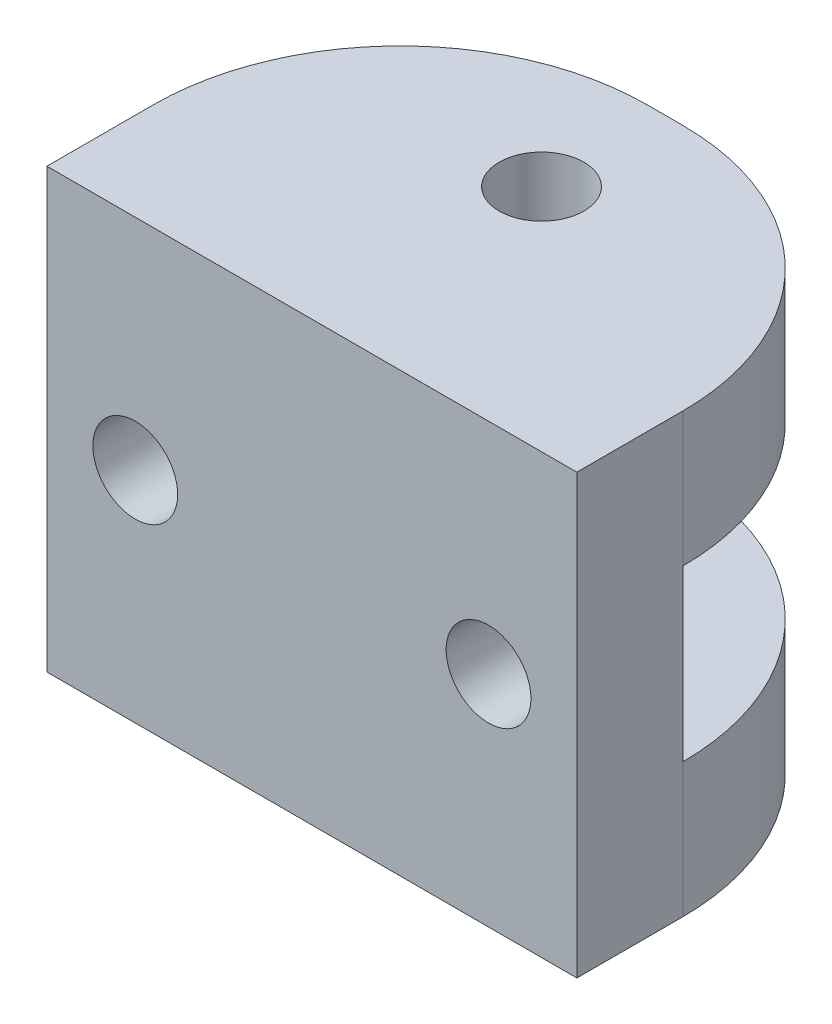
SolidWorks part; units mm, degrees
ref_plane "Front Plane" through (0, 0, 0) normal (0, 0, 1) x (1, 0, 0)
ref_plane "Top Plane" through (0, 0, 0) normal (0, 1, 0) x (1, 0, 0)
ref_plane "Right Plane" through (0, 0, 0) normal (1, 0, 0) x (0, 0, -1)
sketch "Sketch1" plane through (0, 0, 0) normal (1, 0, 0) x (0, 0, -1)
  line L0 (50, 62) -> (50, 43)
  line L1 (0, 0) -> (50, 0)
  line L2 (0, 0) -> (0, 62)
  line L3 (0, 62) -> (50, 62)
  line L5 (50, 43) -> (15, 43)
  line L6 (15, 43) -> (15, 19)
  line L7 (15, 19) -> (50, 19)
  line L8 (50, 19) -> (50, 0)
  dimension "D1" = 24
  dimension "D2" = 62
  dimension "D3" = 35
  dimension "D4" = 50
extrude "Boss-Extrude1" add sketch "Sketch1" along normal blind 75
sketch "Sketch2" plane through (0, 0, 0) normal (0, 0, 1) x (1, 0, 0)
  line L0 (0, 31) -> (75, 31) construction
  line L1 (0, 62) -> (0, 0) construction
  line L2 (75, 62) -> (75, 0) construction
  circle A0 centre (62.5, 31) radius 6
  circle A1 centre (12.5, 31) radius 6
  point P10 (37.5, 31)
  dimension "D3" = 12
  dimension "D1" = 50
  dimension "D2" = 25
extrude "Cut-Extrude1" cut sketch "Sketch2" against normal through all
sketch "Sketch3" plane through (0, 62, 0) normal (0, 1, 0) x (1, 0, 0)
  line L0 (0, 32.5) -> (75, 32.5) construction
  line L1 (0, 50) -> (0, 0) construction
  line L2 (75, 50) -> (75, 0) construction
  line L3 (75, 50) -> (0, 50) construction
  circle A0 centre (37.5, 32.5) radius 6
  dimension "D2" = 12
  dimension "D1" = 17.5
extrude "Cut-Extrude2" cut sketch "Sketch3" against normal through all
fillet "Fillet1" radius 35 4 edges at (75, 9.5, -50) (0, 9.5, -50) (0, 52.5, -50) (75, 52.5, -50)
equation "\"mbtOD\" = 500"
equation "\"mbtT\" = 6"
equation "\"mbtL\" = 3000"
equation "\"mbtFlangeOD\" = 650"
equation "\"mbtFlangeT\" = 12"
equation "\"mbtFlangeBoltCircleDia\" = 650"
equation "\"mbtFlangeHoleDia\" = 12"
equation "\"mbtOringSize\" = 10 "
equation "\"mbtOringDia\" = 620"
equation "\"mbtWidth\" = 2250"
equation "\"skiWidth\" = 1250"
equation "\"D1@Sketch1\"=\"mbtFlangeT\"+12mm"
equation "\"D2@Sketch1\"=\"mbtFlangeT\"+50mm"
